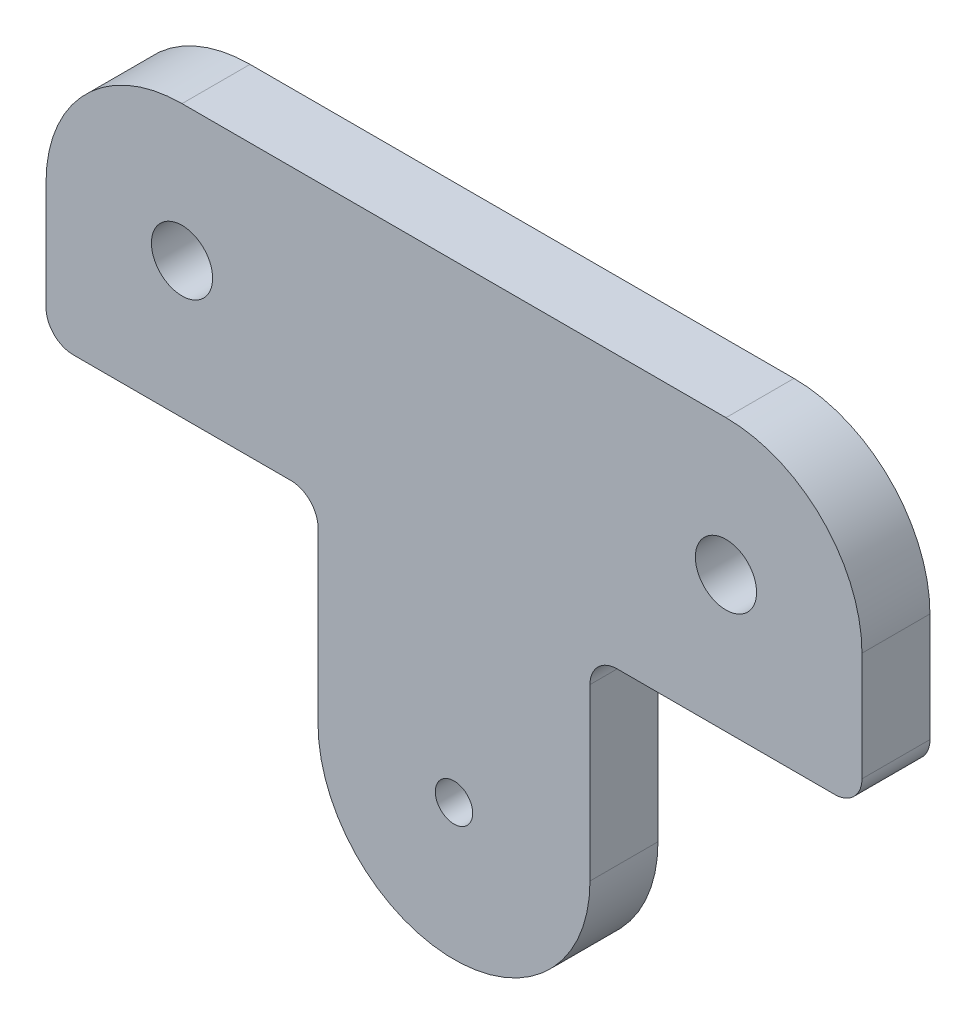
SolidWorks part; units mm, degrees
ref_plane "Front Plane" through (0, 0, 0) normal (0, 0, 1) x (1, 0, 0)
ref_plane "Top Plane" through (0, 0, 0) normal (0, 1, 0) x (1, 0, 0)
ref_plane "Right Plane" through (0, 0, 0) normal (1, 0, 0) x (0, 0, -1)
sketch "Sketch1" plane through (0, 0, 0) normal (0, 0, 1) x (1, 0, 0)
  line L10 (-2.5442, 2.54) -> (-2.5442, -1.524)
  line L11 (-1.5282, -2.54) -> (6.5998, -2.54)
  line L12 (7.6158, -3.556) -> (7.6158, -9.91)
  line L13 (27.9358, 2.54) -> (27.9358, -1.524)
  line L14 (26.9198, -2.54) -> (18.7918, -2.54)
  line L15 (17.7758, -3.556) -> (17.7758, -9.91)
  line L16 (12.6958, 2.54) -> (12.6958, -9.91) construction
  line L18 (2.5358, 7.62) -> (22.8558, 7.62)
  circle A7 centre (2.5358, 2.54) radius 1.143
  circle A8 centre (12.6958, -9.91) radius 0.6985
  circle A9 centre (22.8558, 2.54) radius 1.143
  arc A10 (7.6158, -9.91) -> (17.7758, -9.91) centre (12.6958, -9.91) ccw
  arc A11 (-2.5442, 2.54) -> (2.5358, 7.62) centre (2.5358, 2.54) cw
  arc A12 (22.8558, 7.62) -> (27.9358, 2.54) centre (22.8558, 2.54) cw
  arc A13 (27.9358, -1.524) -> (26.9198, -2.54) centre (26.9198, -1.524) cw
  arc A14 (6.5998, -2.54) -> (7.6158, -3.556) centre (6.5998, -3.556) cw
  arc A15 (18.7918, -2.54) -> (17.7758, -3.556) centre (18.7918, -3.556) ccw
  arc A18 (-2.5442, -1.524) -> (-1.5282, -2.54) centre (-1.5282, -1.524) ccw
  dimension "D4" = 5.08
  dimension "D6" = 1.397
  dimension "D7" = 2.286
  dimension "D8" = 5.08
  dimension "D9" = 5.08
  dimension "D10" = 5.08
  dimension "D11" = 1.016
  dimension "D12" = 20.32
  dimension "D5" = 2.286
  dimension "D3" = 12.45
extrude "Boss-Extrude1" add sketch "Sketch1" along normal blind 2.54
